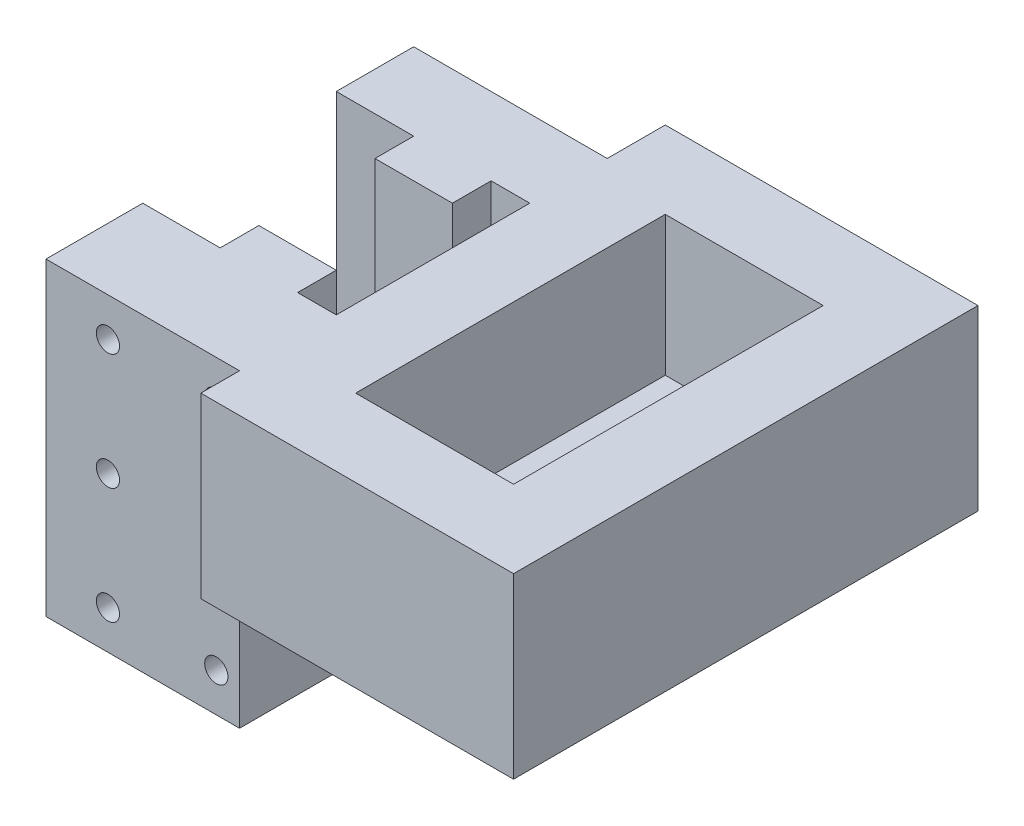
SolidWorks part; units mm, degrees
ref_plane "Front Plane" through (0, 0, 0) normal (0, 0, 1) x (1, 0, 0)
ref_plane "Top Plane" through (0, 0, 0) normal (0, 1, 0) x (1, 0, 0)
ref_plane "Right Plane" through (0, 0, 0) normal (1, 0, 0) x (0, 0, -1)
sketch "Sketch1" plane through (0, 0, 0) normal (0, 1, 0) x (1, 0, 0)
  line L0 (20.2, 30) -> (-20.2, 30)
  line L1 (10.2, -20) -> (-10.2, -20)
  line L2 (10.2, -20) -> (10.2, 20)
  line L3 (10.2, 20) -> (-10.2, 20)
  line L4 (-10.2, -20) -> (-10.2, 20)
  line L5 (10.2, -20) -> (-10.2, 20) construction
  line L6 (10.2, 20) -> (-10.2, -20) construction
  line L7 (-20.2, -30) -> (-20.2, 30)
  line L8 (20.2, -30) -> (-20.2, -30)
  line L9 (20.2, -30) -> (20.2, 30)
  point P0 (0, 0)
  dimension "D1" = 40
  dimension "D2" = 20.4
  dimension "D3" = 10
extrude "Boss-Extrude1" add sketch "Sketch1" along normal blind 18
sketch "Sketch2" plane through (0, 0, 0) normal (0, -1, 0) x (1, 0, 0)
  line L1 (20.2, -30) -> (-20.2, -30)
  line L2 (20.2, -30) -> (20.2, 30)
  line L3 (20.2, 30) -> (-20.2, 30)
  line L4 (-20.2, -30) -> (-20.2, 30)
  line L5 (20.2, -30) -> (-20.2, 30) construction
  line L6 (20.2, 30) -> (-20.2, -30) construction
  point P0 (0, 0)
extrude "Boss-Extrude2" add sketch "Sketch2" along normal blind 5
sketch "Sketch4" plane through (0, 18, 0) normal (0, 1, 0) x (1, 0, 0)
  line L0 (-20.2, 22.5) -> (-45.2, 22.5)
  line L2 (-20.2, 30) -> (-20.2, -30) construction
  line L3 (-45.2, 22.5) -> (-45.2, 12.5)
  line L4 (-45.2, 12.5) -> (-35.2, 12.5)
  line L5 (-35.2, 12.5) -> (-35.2, 7.5)
  line L6 (-35.2, 7.5) -> (-25.2, 7.5)
  line L7 (-25.2, 7.5) -> (-25.2, 12.5)
  line L8 (-25.2, 12.5) -> (-20.2, 12.5)
  line L9 (-20.2, 12.5) -> (-20.2, 22.5)
  line L10 (0, 0) -> (-50.5166, 0) construction
  line L11 (-20.2, -12.5) -> (-20.2, -22.5)
  line L12 (-25.2, -12.5) -> (-20.2, -12.5)
  line L13 (-25.2, -7.5) -> (-25.2, -12.5)
  line L14 (-35.2, -7.5) -> (-25.2, -7.5)
  line L15 (-35.2, -12.5) -> (-35.2, -7.5)
  line L16 (-45.2, -12.5) -> (-35.2, -12.5)
  line L17 (-45.2, -22.5) -> (-45.2, -12.5)
  line L18 (-20.2, -22.5) -> (-45.2, -22.5)
  dimension "D1" = 5
  dimension "D2" = 25
  dimension "D3" = 5
  dimension "D4" = 10
  dimension "D5" = 10
  dimension "D6" = 25
extrude "Boss-Extrude3" add sketch "Sketch4" against normal blind 40
sketch "Sketch5" plane through (0, 0, 22.5) normal (0, 0, 1) x (1, 0, 0)
  line L1 (-45.2, 18) -> (-20.2, 18)
  line L2 (-45.2, 18) -> (-45.2, -22)
  line L3 (-45.2, -22) -> (-20.2, -22)
  line L4 (-20.2, 18) -> (-20.2, -22)
  circle A0 centre (-37.2, 13) radius 1.5
  circle A1 centre (-23.2, 13) radius 1.5
  circle A2 centre (-37.2, -2) radius 1.5
  circle A3 centre (-23.2, -2) radius 1.5
  circle A4 centre (-37.2, -17) radius 1.5
  circle A5 centre (-23.2, -17) radius 1.5
  dimension "D1" = 3
  dimension "D4" = 3
  dimension "D2" = 2
  dimension "D3" = 3
  dimension "D5" = 5
  dimension "D6" = 3
extrude "Boss-Extrude4" add sketch "Sketch5" along normal blind 2.5
